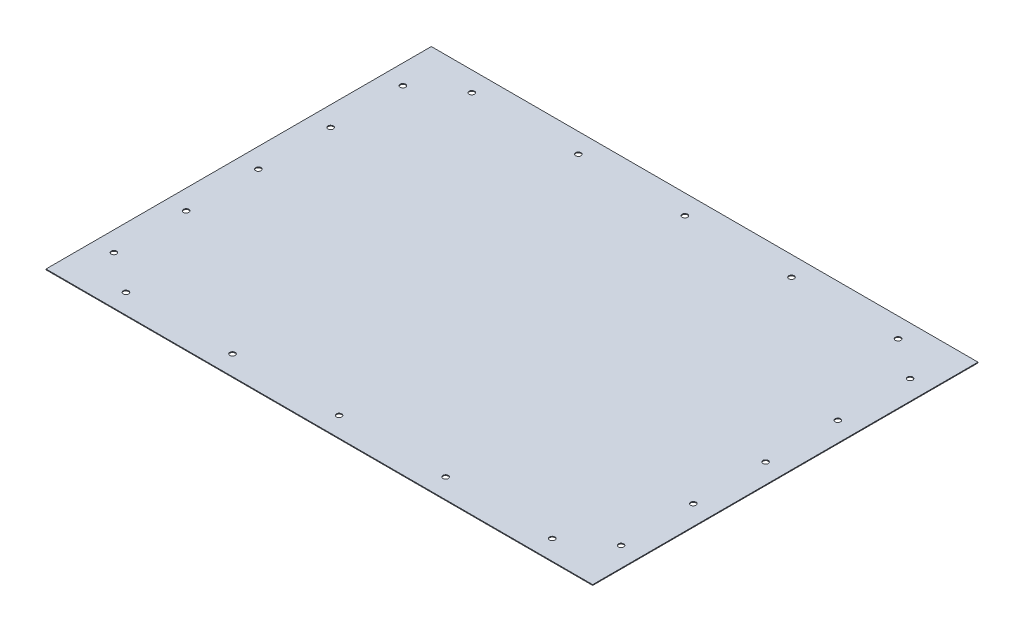
SolidWorks part; units mm, degrees
ref_plane "前视" through (0, 0, 0) normal (0, 0, 1) x (1, 0, 0)
ref_plane "上视" through (0, 0, 0) normal (0, 1, 0) x (1, 0, 0)
ref_plane "右视" through (0, 0, 0) normal (1, 0, 0) x (0, 0, -1)
sketch "Sketch1" plane through (0, 0, 0) normal (0, 1, 0) x (1, 0, 0)
  line L1 (-212.9006, 133.2391) -> (241.0994, 133.2391)
  line L2 (-212.9006, 133.2391) -> (-212.9006, -186.7609)
  line L3 (-212.9006, -186.7609) -> (241.0994, -186.7609)
  line L4 (241.0994, 133.2391) -> (241.0994, -186.7609)
  dimension "D1" = 454
  dimension "D2" = 320
extrude "Boss-Extrude1" add sketch "Sketch1" along normal blind 0.635 contours L1 L4 L3 L2
sketch "Sketch2" plane through (0, 0.635, 0) normal (0, 1, 0) x (1, 0, 0)
  line L0 (-212.9006, -186.7609) -> (241.0994, -186.7609) construction
  line L1 (-212.9006, 133.2391) -> (-212.9006, -186.7609) construction
  circle A0 centre (-162.9006, -170.3609) radius 2.248
  point P0 (-162.9006, -170.3609)
  dimension "D3" = 4.496
  dimension "D1" = 16.4
  dimension "D2" = 50
extrude "Cut-Extrude2" cut sketch "Sketch2" against normal through all
pattern_linear "LPattern1" count 5 spacing 88.5 along (1, 0, 0) of "Cut-Extrude2"
ref_plane "Plane1" through (0, 0, 26.7609) normal (0, 0, -1) x (-1, 0, 0)
mirror "Mirror1" about plane through (0, 0, 26.7609) normal (0, 0, -1) of "LPattern1", "Cut-Extrude2"
sketch "Sketch3" plane through (0, 0.635, 0) normal (0, 1, 0) x (1, 0, 0)
  line L0 (-212.9006, -186.7609) -> (241.0994, -186.7609) construction
  line L1 (-212.9006, 133.2391) -> (-212.9006, -186.7609) construction
  circle A0 centre (-196.5006, -146.7609) radius 2.248
  point P0 (-196.5006, -146.7609)
  dimension "D3" = 4.496
  dimension "D1" = 40
  dimension "D2" = 16.4
extrude "Cut-Extrude3" cut sketch "Sketch3" against normal blind 10
pattern_linear "LPattern2" count 5 spacing 60 along (0, 0, -1) of "Cut-Extrude3"
ref_plane "Plane2" through (14.0994, 0, 0) normal (-1, 0, 0) x (0, 0, 1)
mirror "Mirror2" about plane through (14.0994, 0, 0) normal (-1, 0, 0) of "LPattern2", "Cut-Extrude3"
